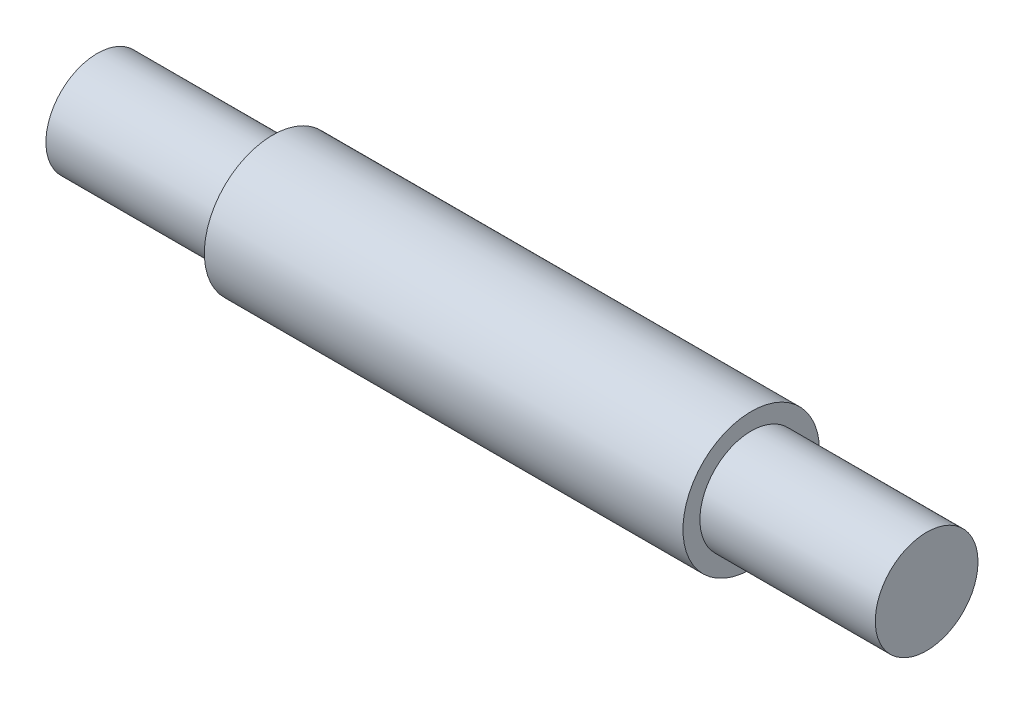
SolidWorks part; units mm, degrees
ref_plane "Front Plane" through (0, 0, 0) normal (0, 0, 1) x (1, 0, 0)
ref_plane "Top Plane" through (0, 0, 0) normal (0, 1, 0) x (1, 0, 0)
ref_plane "Right Plane" through (0, 0, 0) normal (1, 0, 0) x (0, 0, -1)
sketch "Sketch1" plane through (0, 0, 0) normal (1, 0, 0) x (0, 0, -1)
  circle A0 centre (0, 0) radius 3.175
  dimension "D1" = 6.35
extrude "Boss-Extrude1" add sketch "Sketch1" along normal mid plane 38.5572
sketch "Sketch2" plane through (19.2786, 0, 0) normal (1, 0, 0) x (0, 0, -1)
  circle A0 centre (0, 0) radius 3.175
  circle A1 centre (0, 0) radius 2.3876
  dimension "D1" = 4.7752
extrude "Cut-Extrude1" cut sketch "Sketch2" against normal blind 8.1534
mirror "Mirror1" about plane through (0, 0, 0) normal (1, 0, 0) of "Cut-Extrude1"
